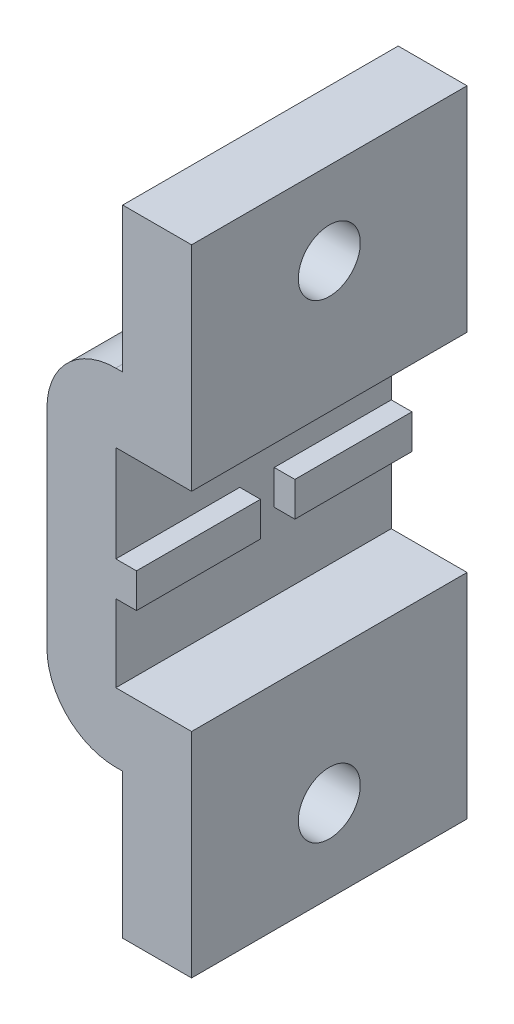
SolidWorks part; units mm, degrees
ref_plane "Piano frontale" through (0, 0, 0) normal (0, 0, 1) x (1, 0, 0)
ref_plane "Piano superiore" through (0, 0, 0) normal (0, 1, 0) x (1, 0, 0)
ref_plane "Piano destro" through (0, 0, 0) normal (1, 0, 0) x (0, 0, -1)
sketch "Schizzo1" plane through (0, 0, 0) normal (0, 0, 1) x (1, 0, 0)
  line L0 (0, 30.6) -> (-5, 30.6)
  line L1 (-5, 30.6) -> (-5, 20.1)
  line L2 (-5, 20.1) -> (-10.5, 20.1)
  line L3 (-10.5, 20.1) -> (-10.5, -5)
  line L4 (-10.5, -5) -> (-5, -5)
  line L5 (-5, -5) -> (-5, -15.5)
  line L6 (-5, -15.5) -> (0, -15.5)
  line L7 (0, -15.5) -> (0, 0)
  line L8 (0, 0) -> (-5.5, 0)
  line L9 (-5.5, 0) -> (-5.5, 15.1)
  line L10 (-5.5, 15.1) -> (0, 15.1)
  line L11 (0, 15.1) -> (0, 30.6)
  dimension "D1" = 46.1
  dimension "D2" = 15.5
  dimension "D3" = 15.5
  dimension "D4" = 5
  dimension "D5" = 5
  dimension "D6" = 5
  dimension "D7" = 5
  dimension "D8" = 5
  dimension "D9" = 5.5
extrude "Estrusione-Estrusione1" add sketch "Schizzo1" along normal blind 20 contours L1 L2 L3 L4 L5 L6 L7 L8 L9 L10 L11 L0
hole_wizard "M4 Clearance Hole1" positions "Schizzo2" profile "Schizzo3" hole size "M4" standard "ISO" end condition up to next
sketch "Schizzo2" plane through (-5, 0, 0) normal (-1, 0, 0) x (0, 0, 1)
  line L0 (10, 30.6) -> (10, -15.5) construction
  line L1 (20, 30.6) -> (0, 30.6) construction
  line L2 (20, -15.5) -> (0, -15.5) construction
  point P0 (10, 24.6)
  point P2 (10, -9.5)
  dimension "D1" = 6
  dimension "D2" = 6
sketch "Schizzo3" plane through (-5, 24.6, 10) normal (0, 1, 0) x (0, 0, 1)
  line L0 (0, 0) -> (0, 5)
  line L1 (0, 5) -> (2.25, 5)
  line L2 (2.25, 5) -> (2.25, 0)
  line L5 (2.25, 0) -> (0, 0)
  line L11 (0, -6.35) -> (0, 107.95) construction
  dimension "Thru Hole Dia." = 4.5
  dimension "Thru Hole Depth" = 5
fillet "Raccordo1" radius 5 2 edges at (-10.5, -5, 10) (-10.5, 20.1, 10)
sketch "Schizzo4" plane through (-5.5, 0, 0) normal (1, 0, 0) x (0, 0, -1)
  line L0 (-20, 0) -> (-20, 15.1) construction
  line L1 (-20, 5.6) -> (-11, 5.6)
  line L2 (-20, 5.6) -> (-20, 8.1)
  line L3 (-20, 8.1) -> (-11, 8.1)
  line L4 (-11, 5.6) -> (-11, 8.1)
  line L5 (0, 0) -> (0, 15.1) construction
  line L6 (0, 5.6) -> (-8.5, 5.6)
  line L7 (0, 5.6) -> (0, 8.1)
  line L8 (0, 8.1) -> (-8.5, 8.1)
  line L9 (-8.5, 5.6) -> (-8.5, 8.1)
  line L10 (-20, 15.1) -> (0, 15.1) construction
  line L11 (-20, 15.1) -> (0, 15.1) construction
  dimension "D1" = 9
  dimension "D2" = 2.5
  dimension "D3" = 2.5
  dimension "D4" = 2.5
  dimension "D5" = 7
  dimension "D6" = 7
extrude "Estrusione-Estrusione2" add sketch "Schizzo4" along normal blind 1.5
